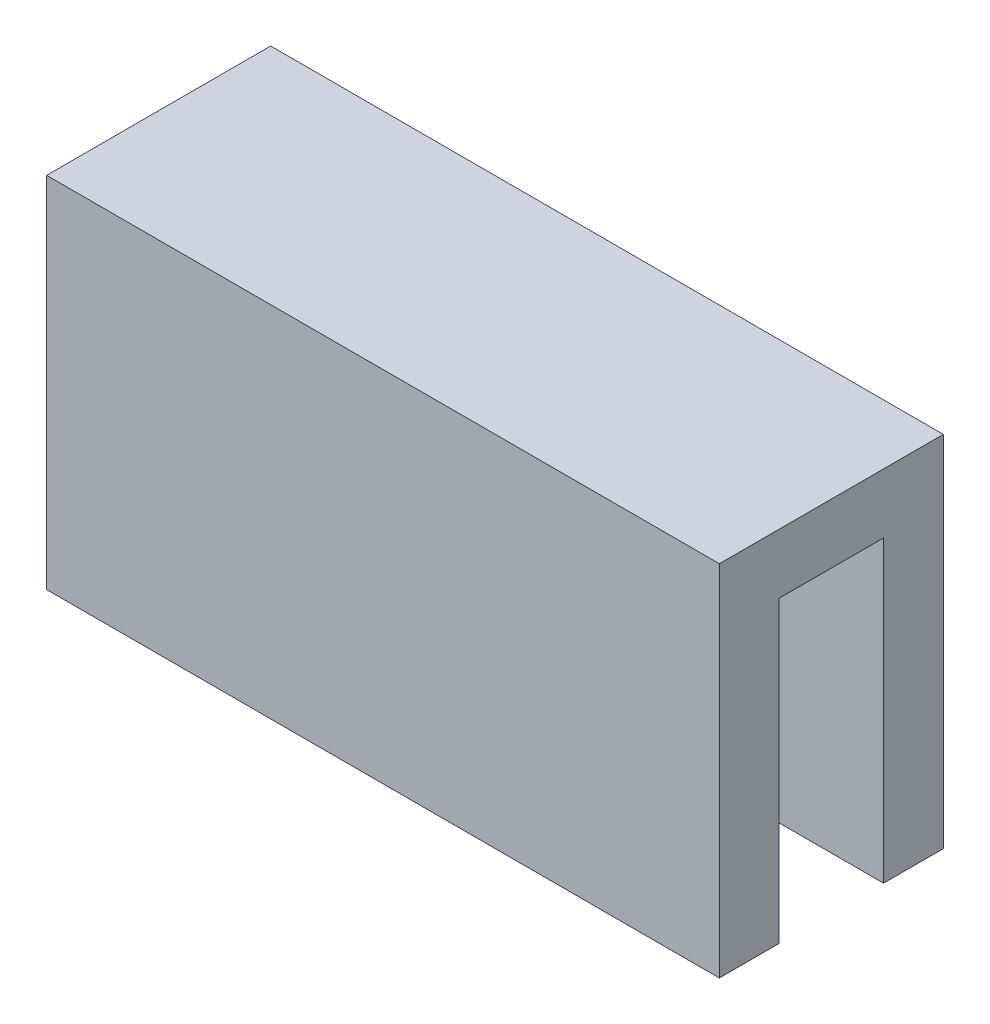
SolidWorks part; units mm, degrees
material "PLA"
ref_plane "Front Plane" through (0, 0, 0) normal (0, 0, 1) x (1, 0, 0)
ref_plane "Top Plane" through (0, 0, 0) normal (0, 1, 0) x (1, 0, 0)
ref_plane "Right Plane" through (0, 0, 0) normal (1, 0, 0) x (0, 0, -1)
sketch "Sketch2" plane through (0, 0, 0) normal (0, 0, 1) x (1, 0, 0)
  line L0 (18, 0) -> (-18, 0) construction
  line L1 (18, 3.2) -> (-18, 3.2)
  line L2 (18, 3.2) -> (18, -16)
  line L3 (18, -16) -> (-18, -16)
  line L4 (-18, 3.2) -> (-18, -16)
  line L5 (0, 3.2) -> (0, -16) construction
  dimension "D1" = 3.2
  dimension "D2" = 36
  dimension "D3" = 16
extrude "Boss-Extrude1" add sketch "Sketch2" along normal mid plane 11.988
sketch "Sketch3" plane through (0, 0, 0) normal (0, 0, 1) x (1, 0, 0)
  line L0 (-18, 3.2) -> (-18, -16) construction
  line L1 (-18, -16) -> (18, -16)
  line L2 (-18, -16) -> (-18, 0)
  line L3 (-18, 0) -> (18, 0)
  line L4 (18, -16) -> (18, 0)
  line L5 (-18, -16) -> (18, -16) construction
  line L6 (18, -16) -> (18, 3.2) construction
  point P5 (0, 0)
  point P10 (0, 0)
extrude "Cut-Extrude1" cut sketch "Sketch3" against normal mid plane 5.588
sketch "Sketch4" plane through (0, 0, -5.994) normal (0, 0, 1) x (1, 0, 0)
  line L0 (0, 3.2) -> (0, -16) construction
  line L1 (-18, -16) -> (18, -16) construction
  line L2 (-3.9, -1.7) -> (3.9, -1.7) construction
  line L3 (18, 3.2) -> (-18, 3.2) construction
  circle A0 centre (11.7, -1.7) radius 3.3
  circle A8 centre (3.9, -1.7) radius 3.3
  circle A9 centre (-3.9, -1.7) radius 3.3
  circle A10 centre (-11.7, -1.7) radius 3.3
  point P2 (0, -1.7)
  point P5 (-26.3333, 2.6915)
  dimension "D1" = 6.6
  dimension "D3" = 1.2
  dimension "D2" = 4
  dimension "D4" = 1.6
extrude "Cut-Extrude2" cut sketch "Sketch4" along normal blind 2.6
sketch "Sketch5" [suppressed] plane through (0, 0, -5.994) normal (0, 0, -1) x (-1, 0, 0)
  line L0 (1.9942, -16) -> (18, 14.0109) construction
  line L1 (18, -16) -> (-18, -16) construction
  line L2 (18, 3.2) -> (18, -16) construction
  line L3 (-18, 3.2) -> (18, -16) construction
  circle A1 centre (6.7875, -1.7) radius 3.3 construction
  text T0 "BACK" font "Segoe UI" height 4
  dimension "D1" = 0.8
extrude "Cut-Extrude3" [suppressed] cut sketch "Sketch5" against normal blind 0.4
sketch "Sketch6" [suppressed] plane through (0, 0, -5.994) normal (0, 0, -1) x (-1, 0, 0)
  line L0 (4.2608, -16) -> (18, 9.7609)
  line L1 (18, 9.7609) -> (18, -16)
  line L2 (18, -16) -> (4.2608, -16)
  line L3 (18, 3.2) -> (18, -16) construction
  line L4 (18, -16) -> (-18, -16) construction
  line L5 (-18, 3.2) -> (18, -16) construction
  circle A0 centre (6.7875, -1.7) radius 3.3 construction
  dimension "D1" = 1.2
extrude "Cut-Extrude4" [suppressed] cut sketch "Sketch6" against normal through all
equation "\"D1@Boss-Extrude1\"=0.22in+(2*3.2mm)"
equation "\"D1@Cut-Extrude1\"=0.22in"
